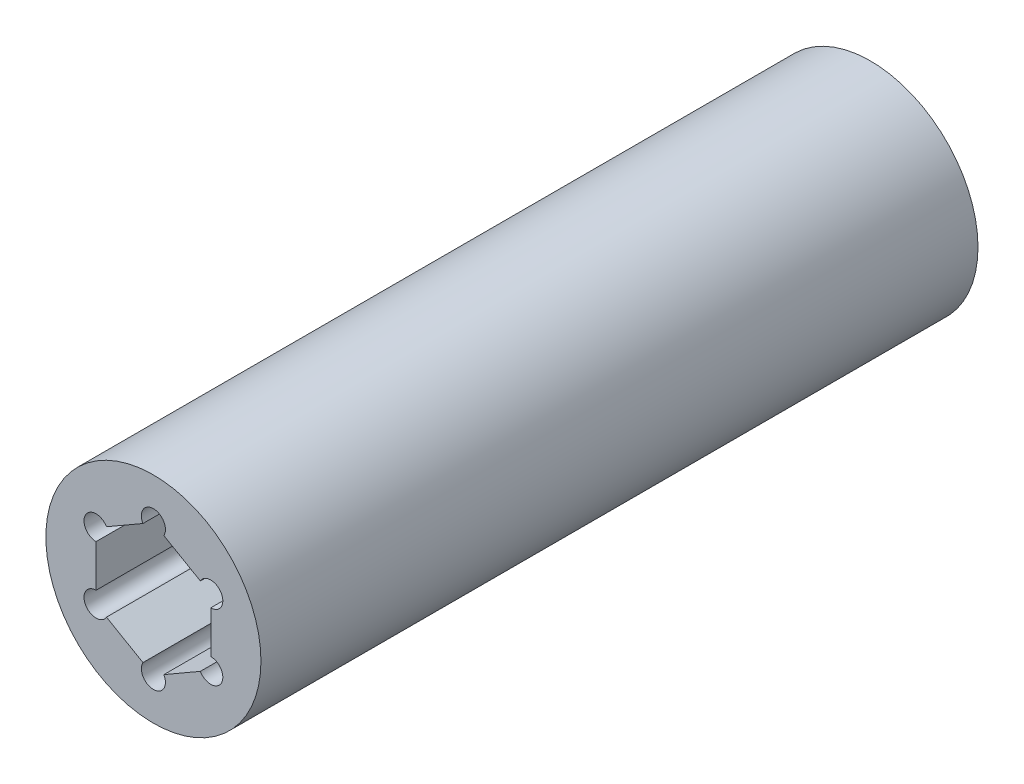
SolidWorks part; units mm, degrees
ref_plane "Front Plane" through (0, 0, 0) normal (0, 0, 1) x (1, 0, 0)
ref_plane "Top Plane" through (0, 0, 0) normal (0, 1, 0) x (1, 0, 0)
ref_plane "Right Plane" through (0, 0, 0) normal (1, 0, 0) x (0, 0, -1)
sketch "Sketch1" plane through (0, 0, 0) normal (0, 0, 1) x (1, 0, 0)
  line L1 (0, 1.8475) -> (-1.6, 0.9238)
  line L2 (-1.6, 0.9238) -> (-1.6, -0.9238)
  line L3 (-1.6, -0.9238) -> (0, -1.8475)
  line L4 (0, -1.8475) -> (1.6, -0.9238)
  line L5 (1.6, -0.9238) -> (1.6, 0.9238)
  line L6 (1.6, 0.9238) -> (0, 1.8475)
  circle A0 centre (0, 0) radius 1.6 construction
  circle A1 centre (0, 0) radius 3
  circle A2 centre (0, 1.8475) radius 0.3359
  circle A3 centre (1.6, 0.9238) radius 0.3359
  circle A4 centre (1.6, -0.9238) radius 0.3359
  circle A5 centre (0, -1.8475) radius 0.3359
  circle A6 centre (-1.6, -0.9238) radius 0.3359
  circle A7 centre (-1.6, 0.9238) radius 0.3359
  point P24 (0, 0)
  dimension "D2" = 6
  dimension "D3" = 6
  dimension "D1" = 3.2
extrude "Boss-Extrude1" add sketch "Sketch1" along normal blind 20 contours A1 A7 L1 A2 L6 A3 L5 A4 L4 A5 L3 A6 L2
